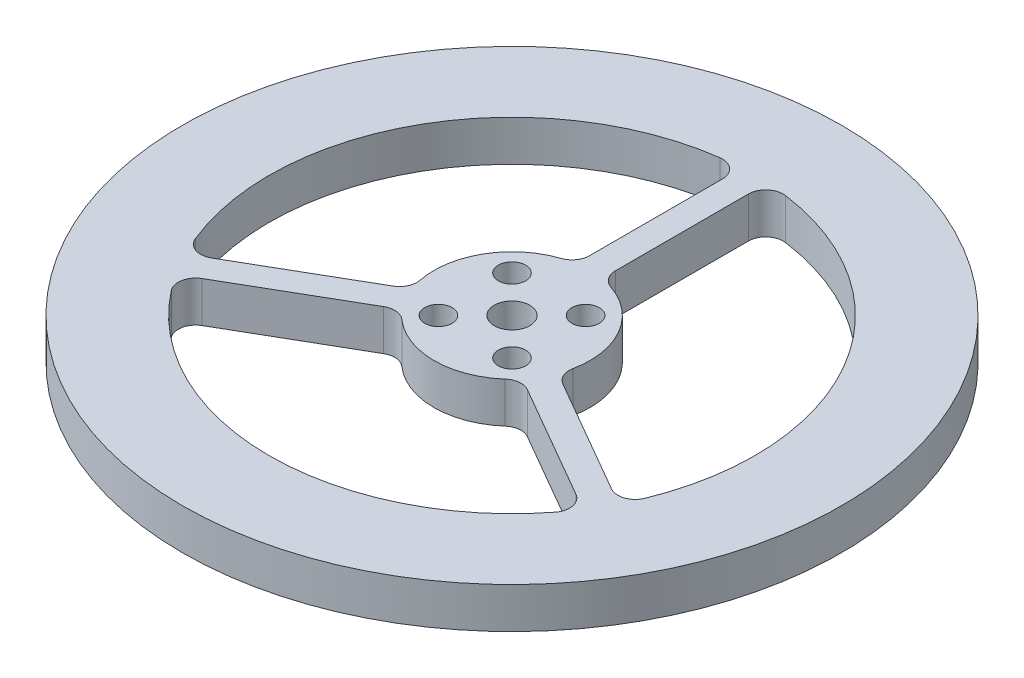
SolidWorks part; units mm, degrees
ref_plane "Front Plane" through (0, 0, 0) normal (0, 0, 1) x (1, 0, 0)
ref_plane "Top Plane" through (0, 0, 0) normal (0, 1, 0) x (1, 0, 0)
ref_plane "Right Plane" through (0, 0, 0) normal (1, 0, 0) x (0, 0, -1)
sketch "Sketch1" plane through (0, 0, 0) normal (0, 1, 0) x (1, 0, 0)
  circle A40 centre (0, 0) radius 38 construction
  circle A41 centre (0, 0) radius 28 construction
  circle A44 centre (0, 0) radius 28
  circle A45 centre (0, 0) radius 38
  dimension "D2" = 76
  dimension "D3" = 56
  dimension "D15" = 76
  dimension "D16" = 56
extrude "Boss-Extrude1" add sketch "Sketch1" along normal blind 4.7
sketch "Sketch2" plane through (0, 0, 0) normal (0, 1, 0) x (1, 0, 0)
  line L6 (-4.2426, 4.2426) -> (4.2426, -4.2426) construction
  line L7 (-4.2426, -4.2426) -> (4.2426, 4.2426) construction
  circle A7 centre (0, 0) radius 2.05
  circle A20 centre (-4.2426, 4.2426) radius 1.575
  circle A21 centre (-4.2426, -4.2426) radius 1.575
  circle A22 centre (4.2426, -4.2426) radius 1.575
  circle A23 centre (4.2426, 4.2426) radius 1.575
  circle A36 centre (-4.2426, -4.2426) radius 2.95 construction
  circle A37 centre (-4.2426, 4.2426) radius 2.95 construction
  circle A38 centre (4.2426, -4.2426) radius 2.95 construction
  circle A39 centre (4.2426, 4.2426) radius 2.95 construction
  circle A42 centre (0, 0) radius 9
  point P44 (0, 0)
  point P45 (0, 0)
  point P55 (0, 0)
  dimension "D2" = 4.1
  dimension "D3" = 18
  dimension "D4" = 3.15
  dimension "D5" = 12
  dimension "D13" = 5.9
extrude "Boss-Extrude2" add sketch "Sketch2" along normal up to surface (4.7 mm away) separate body up to face at (0, 4.7, 38)
sketch "Sketch3" plane through (0, 0, 0) normal (0, 1, 0) x (1, 0, 0)
  line L0 (0, 0) -> (0, 33) construction
  line L1 (-1.5, 29) -> (-1.5, 8.8741)
  line L2 (1.5, 29) -> (1.5, 8.8741)
  line L3 (-1.5, 15) -> (1.5, 15) construction
  line L4 (-1.5, 8.8741) -> (1.5, 8.8741)
  line L5 (-1.5, 29) -> (1.5, 29)
  line L6 (25.8647, -13.201) -> (24.3647, -15.799)
  line L7 (24.3647, -15.799) -> (6.9352, -5.7361)
  line L8 (8.4352, -3.138) -> (6.9352, -5.7361)
  line L9 (25.8647, -13.201) -> (8.4352, -3.138)
  line L10 (13.7404, -6.201) -> (12.2404, -8.799) construction
  line L11 (-24.3647, -15.799) -> (-25.8647, -13.201)
  line L12 (-25.8647, -13.201) -> (-8.4352, -3.138)
  line L13 (-6.9352, -5.7361) -> (-8.4352, -3.138)
  line L14 (-24.3647, -15.799) -> (-6.9352, -5.7361)
  line L15 (-12.2404, -8.799) -> (-13.7404, -6.201) construction
  circle A0 centre (0, 0) radius 9 construction
  point P9 (0, 15)
  point P25 (0, 0)
  dimension "D1" = 3
  dimension "D2" = 3
extrude "Boss-Extrude3" add sketch "Sketch3" along normal up to surface (4.7 mm away) up to face at (0, 4.7, 38)
fillet "Fillet1" radius 2 6 edges at (24.9639, 2.35, 12.6809) (23.4639, 2.35, 15.2789) (1.5, 2.35, -27.9598) (-1.5, 2.35, -27.9598) (-24.9639, 2.35, 12.6809) (-23.4639, 2.35, 15.2789)
fillet "Fillet2" radius 2 6 edges at (1.5, 2.35, -8.8741) (-1.5, 2.35, -8.8741) (-8.4352, 2.35, 3.138) (8.4352, 2.35, 3.138) (6.9352, 2.35, 5.7361) (-6.9352, 2.35, 5.7361)
